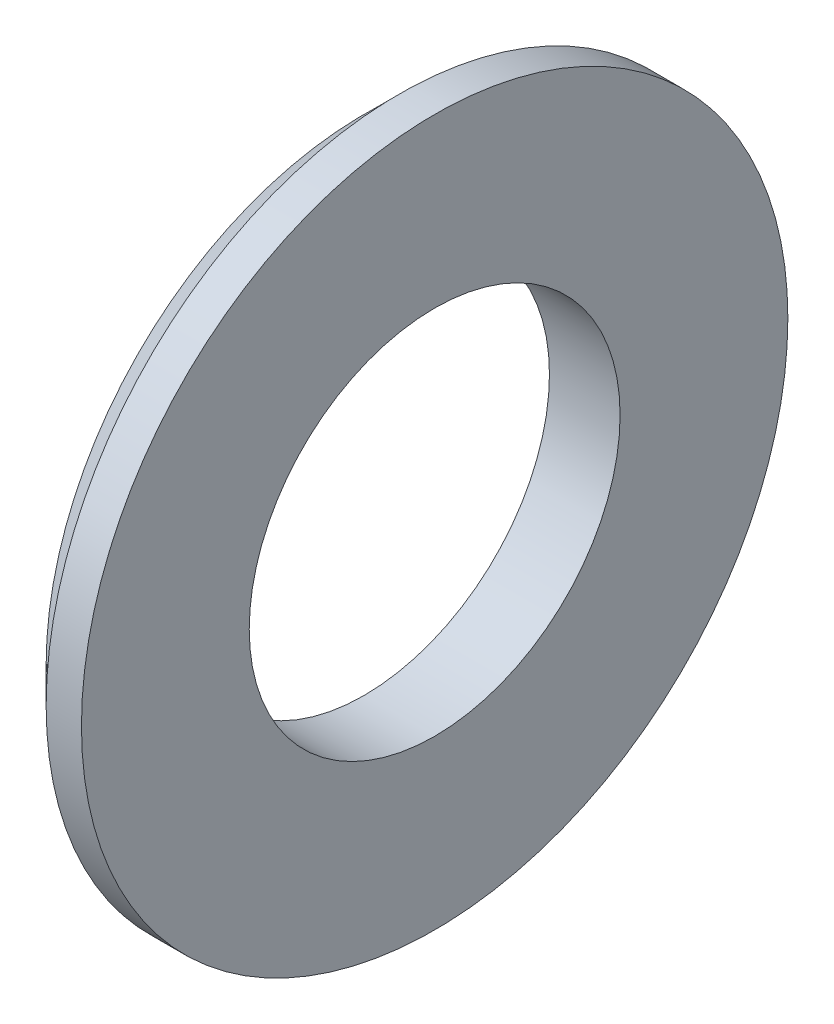
SolidWorks part; units mm, degrees
ref_plane "Plane1" through (0, 0, 0) normal (0, 0, 1) x (1, 0, 0)
ref_plane "Plane2" through (0, 0, 0) normal (0, 1, 0) x (1, 0, 0)
ref_plane "Plane3" through (0, 0, 0) normal (1, 0, 0) x (0, 0, -1)
sketch "Sketch1" plane through (0, 0, 0) normal (0, 0, 1) x (1, 0, 0)
  line L0 (-34.925, 0) -> (9.525, 0) construction
  line L1 (0, 5.25) -> (0, 10)
  line L2 (0, 10) -> (-1, 10)
  line L3 (-2, 9) -> (-2, 5.25)
  line L4 (-2, 5.25) -> (0, 5.25)
  line L5 (-2, 9) -> (-1, 10)
  dimension "Inside_dia" = 10.5
  dimension "Outside_dia" = 20
  dimension "Thickness" = 2
  dimension "D2" = 45
  dimension "D3" = 1
revolve "Base-Revolve" add sketch "Sketch1" angle 360 about L0
equation "\"D3@Sketch1\" = \"Thickness@Sketch1\" * .5"
